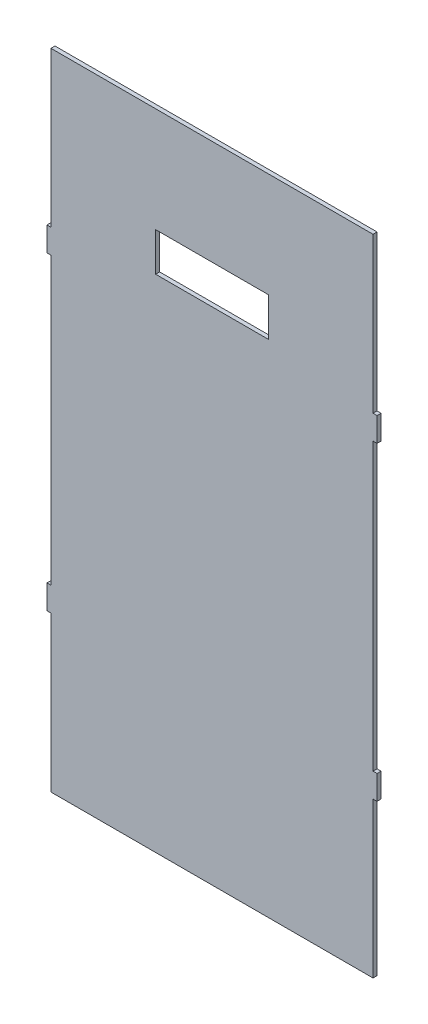
SolidWorks part; units mm, degrees
ref_plane "Plan de face" through (0, 0, 0) normal (0, 0, 1) x (1, 0, 0)
ref_plane "Plan de dessus" through (0, 0, 0) normal (0, 1, 0) x (1, 0, 0)
ref_plane "Plan de droite" through (0, 0, 0) normal (1, 0, 0) x (0, 0, -1)
sketch "Esquisse1" plane through (0, 0, 0) normal (0, 0, 1) x (1, 0, 0)
  line L0 (-150, 0) -> (150, 0) construction
  line L1 (-200, 400) -> (200, 400)
  line L2 (-200, 400) -> (-200, 207.5)
  line L3 (-200, -400) -> (200, -400)
  line L4 (200, 400) -> (200, 207.5)
  line L5 (-200, 400) -> (200, -400) construction
  line L6 (-200, -400) -> (200, 400) construction
  line L7 (205, -177.5) -> (200, -177.5)
  line L8 (205, 207.5) -> (200, 207.5)
  line L9 (205, 207.5) -> (205, 177.5)
  line L10 (205, 177.5) -> (200, 177.5)
  line L12 (205, 207.5) -> (200, 177.5) construction
  line L13 (205, 177.5) -> (200, 207.5) construction
  line L15 (205, -207.5) -> (200, -207.5)
  line L16 (205, -207.5) -> (205, -177.5)
  line L17 (0, 400) -> (0, -400) construction
  line L18 (-205, -207.5) -> (-205, -177.5)
  line L19 (-205, -207.5) -> (-200, -207.5)
  line L21 (-205, -177.5) -> (-200, -177.5)
  line L22 (-205, 177.5) -> (-200, 177.5)
  line L24 (-205, 207.5) -> (-200, 207.5)
  line L25 (-205, 207.5) -> (-205, 177.5)
  line L26 (-200, 177.5) -> (-200, -177.5)
  line L27 (200, 177.5) -> (200, -177.5)
  line L28 (200, -207.5) -> (200, -400)
  line L29 (-200, -207.5) -> (-200, -400)
  point P0 (0, 0)
  point P6 (202.5, 192.5)
  point P9 (0, 0)
  point P21 (0, 0)
  dimension "D1" = 400
  dimension "D2" = 800
  dimension "D3" = 5
  dimension "D4" = 30
  dimension "D5" = 192.5
extrude "Boss.-Extru.1" add sketch "Esquisse1" along normal blind 5
sketch "Esquisse2" plane through (0, 0, 5) normal (0, 0, 1) x (1, 0, 0)
  line L0 (-200, 400) -> (-200, 207.5) construction
  line L1 (-70, 222) -> (70, 222)
  line L2 (-70, 222) -> (-70, 270)
  line L3 (-70, 270) -> (70, 270)
  line L4 (70, 222) -> (70, 270)
  line L5 (200, 207.5) -> (200, 400) construction
  line L6 (200, 400) -> (-200, 400) construction
  dimension "D1" = 130
  dimension "D2" = 130
  dimension "D3" = 130
  dimension "D4" = 222
extrude "Enlèv. mat.-Extru.1" cut sketch "Esquisse2" against normal through all
